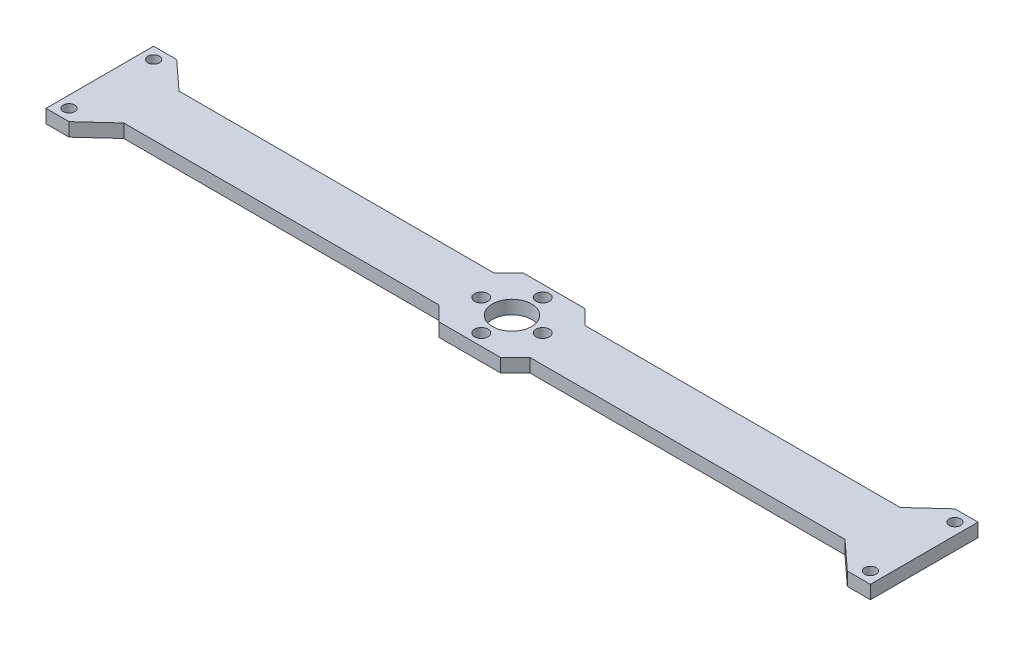
SolidWorks part; units mm, degrees
ref_plane "Front Plane" through (0, 0, 0) normal (0, 0, 1) x (1, 0, 0)
ref_plane "Top Plane" through (0, 0, 0) normal (0, 1, 0) x (1, 0, 0)
ref_plane "Right Plane" through (0, 0, 0) normal (1, 0, 0) x (0, 0, -1)
sketch "Sketch1" plane through (0, 0, 0) normal (0, 1, 0) x (1, 0, 0)
  line L0 (-93.8192, 7.1808) -> (-11.8192, 7.1808)
  line L1 (-11.8192, 7.1808) -> (-8, 11)
  line L2 (-8, 11) -> (8, 11)
  line L3 (8, 11) -> (11.8192, 7.1808)
  line L4 (11.8192, 7.1808) -> (93.8192, 7.1808)
  line L5 (93.8192, 7.1808) -> (101.25, 14)
  line L6 (101.25, 14) -> (107.25, 14)
  line L7 (-107.25, 14) -> (-107.25, -14)
  line L8 (107.25, 14) -> (107.25, -14)
  line L9 (-139.8228, 0) -> (134.4444, 0) construction
  line L10 (-101.25, -14) -> (-93.8192, -7.1808)
  line L11 (-107.25, -14) -> (-101.25, -14)
  line L12 (101.25, -14) -> (107.25, -14)
  line L13 (93.8192, -7.1808) -> (101.25, -14)
  line L14 (11.8192, -7.1808) -> (93.8192, -7.1808)
  line L15 (8, -11) -> (11.8192, -7.1808)
  line L16 (-8, -11) -> (8, -11)
  line L17 (-11.8192, -7.1808) -> (-8, -11)
  line L18 (-107.25, 14) -> (-101.25, 14)
  line L19 (-101.25, 14) -> (-93.8192, 7.1808)
  line L20 (-93.8192, -7.1808) -> (-11.8192, -7.1808)
  circle A0 centre (0, 0) radius 8 construction
  circle A1 centre (-8, 0) radius 1.75
  circle A2 centre (8, 0) radius 1.75
  circle A3 centre (0, 0) radius 5.1
  circle A4 centre (-104.25, -11) radius 1.5
  circle A5 centre (0, 8) radius 1.75
  circle A6 centre (0, -8) radius 1.75
  circle A7 centre (-104.25, 11) radius 1.5
  circle A8 centre (104.25, 11) radius 1.5
  circle A9 centre (104.25, -11) radius 1.5
  point P24 (-107.25, 0)
  point P35 (107.25, 0)
  dimension "D2" = 10.2
  dimension "D3" = 8
  dimension "D4" = 3.5
  dimension "D13" = 3
  dimension "D10" = 8
  dimension "D5" = 16
  dimension "D6" = 11
  dimension "D7" = 82
  dimension "D8" = 6
  dimension "D9" = 14
  dimension "D11" = 214.5
  dimension "D14" = 3
  dimension "D15" = 3
  dimension "D16" = 3
  dimension "D17" = 3
  dimension "D18" = 3
  dimension "D19" = 3
extrude "Boss-Extrude1" add sketch "Sketch1" along normal blind 3.5
